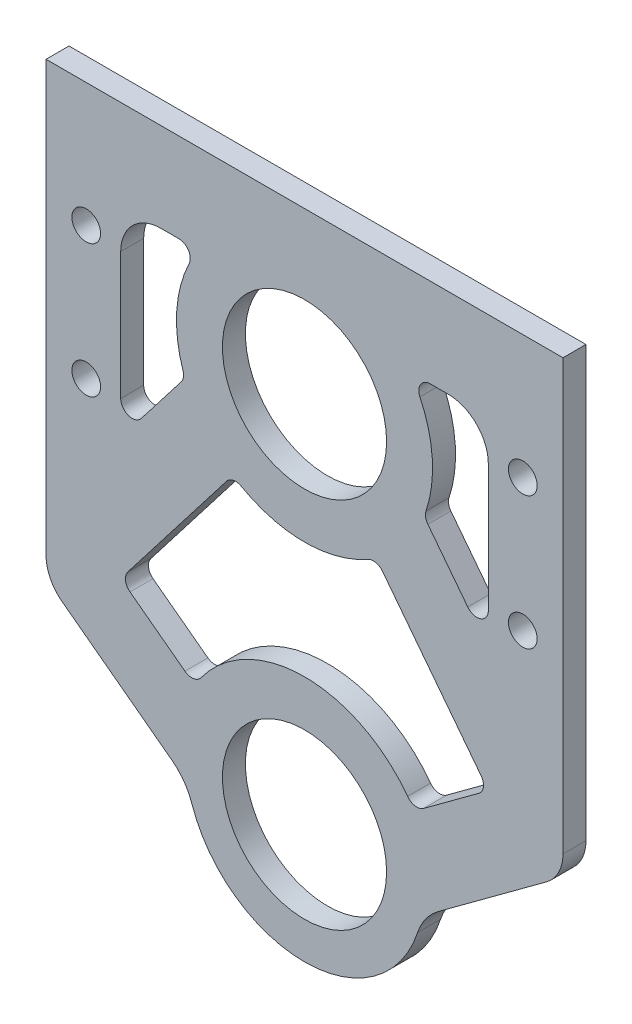
SolidWorks part; units mm, degrees
ref_plane "Front Plane" through (0, 0, 0) normal (0, 0, 1) x (1, 0, 0)
ref_plane "Top Plane" through (0, 0, 0) normal (0, 1, 0) x (1, 0, 0)
ref_plane "Right Plane" through (0, 0, 0) normal (1, 0, 0) x (0, 0, -1)
sketch "Sketch1" plane through (0, 0, 0) normal (0, 0, 1) x (1, 0, 0)
  line L14 (32, 42.3759) -> (32, 77.3868) construction
  line L15 (42.1539, 12.4387) -> (23.2591, -1.4918)
  line L17 (-42.2004, 12.5043) -> (-23.0988, -1.8239)
  line L27 (32, 77.3868) -> (18.4438, 77.3868) construction
  line L42 (-32, 21.1037) -> (-19.1262, 11.447) construction
  line L46 (-32, 21.1037) -> (-12.4722, 46.396) construction
  line L58 (0, 90.3868) -> (0, 50.58) construction
  line L63 (32, 21.1037) -> (12.4722, 46.396) construction
  line L64 (32, 21.1037) -> (19.0572, 11.5615) construction
  line L65 (32, 42.3759) -> (19.4885, 58.5807) construction
  line L66 (32, 42.3759) -> (32, -3.722) construction
  line L67 (61.7198, 20.0015) -> (45, 90.0024) construction
  line L68 (32, 77.3868) -> (32, 42.3759) construction
  line L70 (19.0572, 11.5615) -> (32, 21.1037) construction
  line L71 (32, 21.1037) -> (12.4722, 46.396) construction
  line L73 (18.4438, 77.3868) -> (32, 77.3868) construction
  line L74 (32, 77.3868) -> (32, 42.3759) construction
  line L75 (32, 42.3759) -> (19.4885, 58.5807) construction
  line L76 (-18.4438, 77.3868) -> (-32, 77.3868) construction
  line L80 (-32, 21.1037) -> (-12.4722, 46.396) construction
  line L81 (-19.1262, 11.447) -> (-32, 21.1037) construction
  line L84 (-45, 85.6792) -> (-45, 14.6043) construction
  line L87 (18.4438, 77.3868) -> (32, 77.3868) construction
  line L88 (32, 77.3868) -> (32, 42.3759) construction
  line L89 (32, 42.3759) -> (19.4885, 58.5807) construction
  line L91 (-18.4438, 77.3868) -> (-32, 77.3868) construction
  line L94 (-12.4722, 46.396) -> (-32, 21.1037) construction
  line L95 (-32, 21.1037) -> (-19.1262, 11.447) construction
  line L96 (19.0572, 11.5615) -> (32, 21.1037) construction
  line L97 (32, 21.1037) -> (12.4722, 46.396) construction
  line L100 (-45, 85.6792) -> (-45, 18.104)
  line L102 (45, 90.0024) -> (45, 18.0729)
  line L104 (13.5744, 44.9685) -> (30.7503, 22.7223)
  line L105 (30.3541, 19.8903) -> (20.7396, 12.8018)
  line L107 (-20.8212, 12.7185) -> (-30.3777, 19.8868)
  line L108 (-30.7606, 22.709) -> (-13.5744, 44.9685)
  line L117 (0, 16.192) -> (0, -20) construction
  line L118 (0, 16.192) -> (0, 14.29) construction
  line L119 (32, 77.3868) -> (18.4438, 77.3868) construction
  line L122 (19.4885, 58.5807) -> (32, 42.3759) construction
  line L133 (0, 92.8804) -> (45, 92.8804) construction
  line L138 (21.8952, 77.3868) -> (25, 77.3868)
  line L139 (32, 70.3868) -> (32, 48.2389)
  line L140 (28.4169, 47.0167) -> (21.4744, 56.0086)
  line L141 (-32, 70.3868) -> (-32, 48.2389)
  line L142 (-21.8952, 77.3868) -> (-25, 77.3868)
  line L144 (-28.4169, 47.0167) -> (-21.4744, 56.0086)
  line L145 (-32, 42.3759) -> (-32, -1.9677) construction
  line L146 (62.0434, 0) -> (-79.8138, 0) construction
  line L147 (-45, 92.8804) -> (0, 92.8804) construction
  line L149 (45, 90.0024) -> (45, 92.8804)
  line L150 (45, 92.8804) -> (-45, 92.8804)
  line L151 (-45, 92.8804) -> (-45, 85.6792)
  line L152 (0, 92.8804) -> (0, -31.009) construction
  circle A12 centre (0, 0) radius 14.29 construction
  circle A15 centre (-36.0434, 98.2868) radius 1.3379 construction
  circle A16 centre (36.5212, 98.2868) radius 1.0795 construction
  circle A18 centre (0, 64.87) radius 14.29 construction
  arc A20 (2.2099, 50.7519) -> (-2.2099, 50.7519) centre (0, 0) ccw construction
  circle A45 centre (0, 0) radius 14.29 construction
  arc A52 (11.004, 45.4856) -> (-11.004, 45.4856) centre (0, 64.87) cw
  arc A53 (17.9428, 13.225) -> (-18.0055, 13.1394) centre (0, 0) ccw
  circle A61 centre (0, 64.87) radius 14.29 construction
  circle A68 centre (0, 0) radius 14.29 construction
  circle A69 centre (0, 64.87) radius 14.29 construction
  circle A78 centre (0, 0) radius 14.29
  circle A79 centre (0, 64.87) radius 14.29
  arc A83 (20.0924, 74.5209) -> (21.159, 57.8598) centre (0, 64.87) cw
  arc A84 (-20.0924, 74.5209) -> (-21.159, 57.8598) centre (0, 64.87) ccw
  arc A86 (13.3746, -15.8158) -> (19.6881, -6.4343) centre (0, 0) ccw
  arc A88 (-32, 70.3868) -> (-25, 77.3868) centre (-25, 70.3868) cw
  arc A89 (25, 77.3868) -> (32, 70.3868) centre (25, 70.3868) cw
  arc A90 (-42.2004, 12.5043) -> (-45, 18.104) centre (-38, 18.104) cw
  arc A91 (42.1539, 12.4387) -> (45, 18.0729) centre (38, 18.0729) ccw
  circle A92 centre (0, 0) radius 50.8 construction
  arc A99 (-21.4744, 56.0086) -> (-21.159, 57.8598) centre (-23.0575, 57.2308) ccw
  arc A100 (21.4744, 56.0086) -> (21.159, 57.8598) centre (23.0575, 57.2308) cw
  arc A101 (20.0924, 74.5209) -> (21.8952, 77.3868) centre (21.8952, 75.3868) cw
  arc A102 (-21.8952, 77.3868) -> (-20.0924, 74.5209) centre (-21.8952, 75.3868) cw
  arc A103 (-32, 48.2389) -> (-28.4169, 47.0167) centre (-30, 48.2389) ccw
  arc A104 (32, 48.2389) -> (28.4169, 47.0167) centre (30, 48.2389) cw
  arc A105 (-11.004, 45.4856) -> (-13.5744, 44.9685) centre (-11.9913, 43.7463) ccw
  arc A106 (11.004, 45.4856) -> (13.5744, 44.9685) centre (11.9913, 43.7463) cw
  arc A107 (20.7396, 12.8018) -> (17.9428, 13.225) centre (19.5527, 14.4116) cw
  arc A108 (-20.8212, 12.7185) -> (-18.0055, 13.1394) centre (-19.6211, 14.3184) ccw
  arc A109 (-30.3777, 19.8868) -> (-30.7606, 22.709) centre (-29.1775, 21.4867) cw
  arc A110 (30.7503, 22.7223) -> (30.3541, 19.8903) centre (29.1673, 21.5001) cw
  arc A111 (19.6881, -6.4343) -> (23.2591, -1.4918) centre (29.1933, -9.5407) cw
  arc A112 (13.3746, -15.8158) -> (-19.6247, -6.625) centre (0, 0) cw
  arc A113 (-19.6247, -6.625) -> (-23.0988, -1.8239) centre (-29.0994, -9.8235) ccw
  circle A114 centre (38, 48.2389) radius 2.5
  circle A115 centre (38, 71.3435) radius 2.5
  circle A116 centre (-38, 48.2389) radius 2.5
  circle A117 centre (-38, 71.3435) radius 2.5
  point P18 (0, -29.5208)
  point P35 (0, -21.6734)
  point P38 (-28.4247, 44.1138)
  point P44 (-56.8495, 58.3222)
  point P47 (0, 93.2868)
  point P58 (-28.4247, 11.6788)
  point P74 (0, 80.8916)
  point P84 (-20.8064, 56.8738)
  point P87 (20.8064, 56.8738)
  point P117 (28.4247, 11.6788)
  point P118 (56.8495, 58.3222)
  point P119 (28.4247, 44.1138)
  dimension "D2" = 28.58
  dimension "D3" = 28.58
  dimension "D4" = 101.6
  dimension "D5" = 13
  dimension "D7" = 13
  dimension "D8" = 13
  dimension "D9" = 10
  dimension "D10" = 13
  dimension "D11" = 8
  dimension "D12" = 8
  dimension "D13" = 8
  dimension "D14" = 13
  dimension "D15" = 7
  dimension "D17" = 101.6
  dimension "D18" = 5
  dimension "D20" = 2
  dimension "D21" = 2
  dimension "D22" = 10
  dimension "D19" = 5
  dimension "D6" = 13
  dimension "D16" = 90
extrude "Boss-Extrude1" add sketch "Sketch1" along normal blind 4
